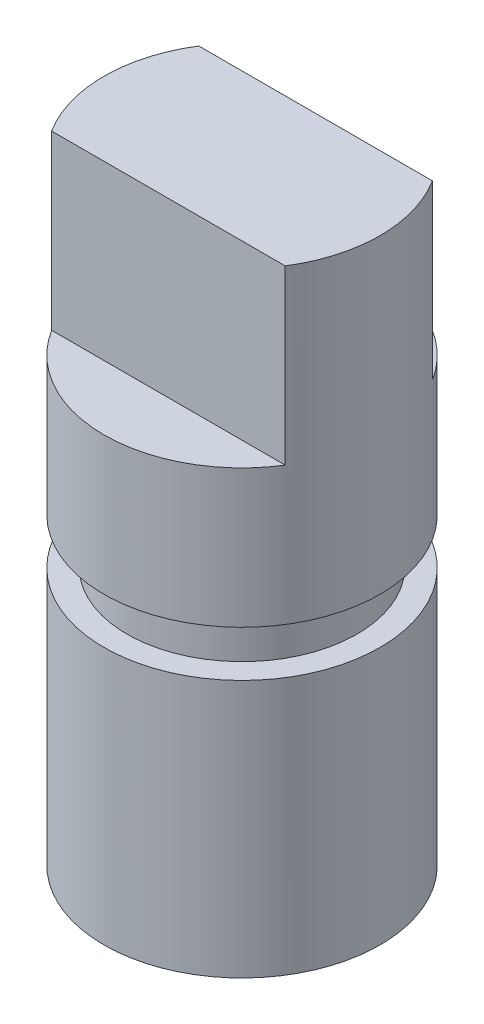
SolidWorks part; units mm, degrees
ref_plane "Front Plane" through (0, 0, 0) normal (0, 0, 1) x (1, 0, 0)
ref_plane "Top Plane" through (0, 0, 0) normal (0, 1, 0) x (1, 0, 0)
ref_plane "Right Plane" through (0, 0, 0) normal (1, 0, 0) x (0, 0, -1)
sketch "Sketch1" plane through (0, 0, 0) normal (0, 1, 0) x (1, 0, 0)
  circle A0 centre (0, 0) radius 3
  dimension "D1" = 6
extrude "Boss-Extrude1" add sketch "Sketch1" along normal blind 9.6
sketch "Sketch2" plane through (0, 0, 0) normal (0, -1, 0) x (1, 0, 0)
  circle A0 centre (0, 0) radius 1.75
  dimension "D1" = 3.5
extrude "Cut-Extrude1" cut sketch "Sketch2" against normal blind 1
sketch "Sketch3" plane through (0, 9.6, 0) normal (0, 1, 0) x (1, 0, 0)
  line L0 (-3, 0) -> (3, 0) construction
  line L1 (-2.5377, -1.6) -> (2.5377, -1.6)
  line L2 (-2.5377, 1.6) -> (2.5377, 1.6)
  line L3 (0, 1.6) -> (0, -1.6) construction
  circle A0 centre (0, 0) radius 3 construction
  arc A1 (2.5377, -1.6) -> (2.5377, 1.6) centre (0, 0) ccw
  arc A2 (-2.5377, 1.6) -> (-2.5377, -1.6) centre (0, 0) ccw
  point P11 (0, 0)
  dimension "D1" = 3.2
extrude "Boss-Extrude2" add sketch "Sketch3" along normal blind 3.75
sketch "Sketch4" plane through (0, 0, 0) normal (1, 0, 0) x (0, 0, -1)
  line L2 (-3, 0) -> (3, 0) construction
  line L3 (-3, 6.6) -> (-2.5, 6.6)
  line L4 (-3, 6.6) -> (-3, 5.6)
  line L5 (-3, 5.6) -> (-2.5, 5.6)
  line L6 (-2.5, 6.6) -> (-2.5, 5.6)
  line L7 (0, 0) -> (0, 15.2894) construction
  point P8 (-2.75, 5.6)
  dimension "D1" = 5.6
  dimension "D2" = 1
  dimension "D3" = 0.5
revolve "Cut-Revolve2" cut sketch "Sketch4" angle 360 about L7
